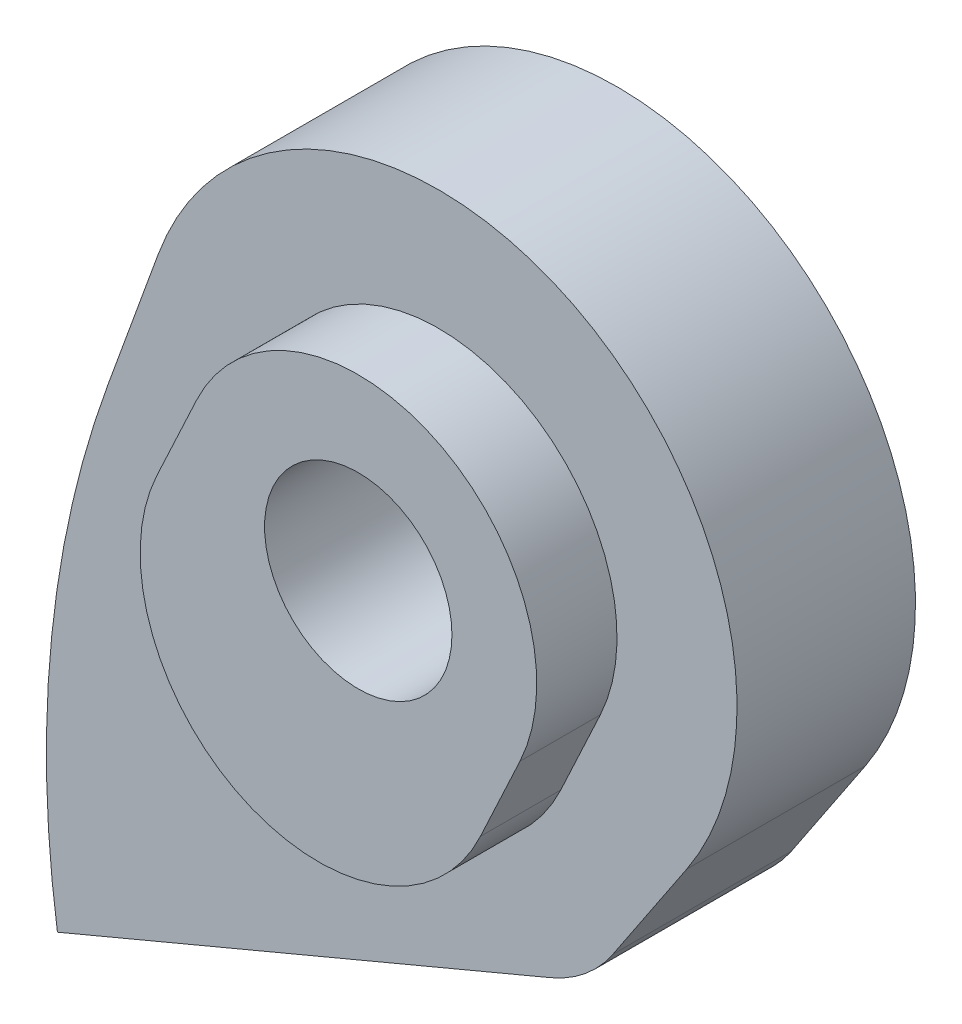
SolidWorks part; units mm, degrees
ref_plane "Front Plane" through (0, 0, 0) normal (0, 0, 1) x (1, 0, 0)
ref_plane "Top Plane" through (0, 0, 0) normal (0, 1, 0) x (1, 0, 0)
ref_plane "Right Plane" through (0, 0, 0) normal (1, 0, 0) x (0, 0, -1)
sketch "Sketch6" plane through (0, 0, 0) normal (0, 0, 1) x (1, 0, 0)
  line L0 (0, 0) -> (40.1809, 0) construction
  line L1 (0, 0) -> (35.507, 92.499) construction
  line L2 (19.3519, 50.4133) -> (0.4719, 63.0164) construction
  line L3 (19.3519, 50.4133) -> (-36.1025, 71.7003) construction
  dimension "D1" = 69
  dimension "D2" = 54
  dimension "D3" = 22.7
  dimension "D4" = 5
sketch "Sketch3" plane through (0, 0, 0) normal (0, 0, 1) x (1, 0, 0)
  line L0 (24.1743, 72.523) -> (120.8717, 72.523) construction
  line L6 (11.8164, 60.2529) -> (11.7284, 60.3116)
  line L7 (7.3748, 53.5992) -> (5.9136, 54.5745)
  line L8 (19.3519, 50.4133) -> (0.4719, 63.0164) construction
  line L9 (-6.1719, 82.4206) -> (-7.2903, 79.3479)
  line L10 (19.3519, 50.4133) -> (13.2479, 41.2693) construction
  line L11 (19.3519, 50.4133) -> (31.6629, 68.8558) construction
  line L12 (4.0204, 73.9337) -> (5.6789, 76.4182)
  line L14 (0.1147, 80.1325) -> (27.1455, 62.0885) construction
  line L15 (0.1147, 80.1325) -> (-7.2903, 79.3479) construction
  line L16 (0.1147, 80.1325) -> (0.1147, 91.1913) construction
  line L17 (0.1147, 80.1325) -> (-6.1719, 82.4206) construction
  arc A0 (13.4996, 47.0498) -> (20.2139, 57.1081) centre (19.3519, 50.4133) ccw
  arc A1 (20.2139, 57.1081) -> (11.8164, 60.2529) centre (22.7223, 76.5904) cw
  arc A2 (13.4996, 47.0498) -> (7.3748, 53.5992) centre (-3.5311, 37.2616) ccw
  arc A3 (11.7284, 60.3116) -> (6.8662, 65.9311) centre (19.4923, 71.9424) cw
  arc A4 (-6.1719, 82.4206) -> (5.6789, 76.4182) centre (0.1147, 80.1325) cw
  arc A5 (6.8662, 65.9311) -> (4.9012, 68.3908) centre (0.6246, 62.9595) ccw
  arc A6 (4.9012, 68.3908) -> (4.0204, 73.9337) centre (7.4585, 71.6386) cw
  arc A7 (5.9136, 54.5745) -> (0.4148, 56.2666) centre (0.3298, 46.2096) ccw
  arc A10 (0.4148, 56.2666) -> (-5.2798, 59.4837) centre (0.4719, 63.0164) cw
  circle A12 centre (19.3519, 50.4133) radius 2.75
  circle A13 centre (0.4719, 63.0164) radius 2.75
  circle A17 centre (0.1147, 80.1325) radius 2.1
  arc A18 (-7.2903, 79.3479) -> (-5.2798, 59.4837) centre (14.2795, 71.4971) ccw
  dimension "D1" = 5.5
  dimension "D2" = 5.5
  dimension "D3" = 4
  dimension "D5" = 4
  dimension "D6" = 4
  dimension "D4" = 4.2
  dimension "D17" = 70
  dimension "D18" = 3.27
  dimension "D14" = 6.69
  dimension "D7" = 3
  dimension "D8" = 4
  dimension "D9" = 3
  dimension "D10" = 4
  dimension "D11" = 19
  dimension "D12" = 19
  dimension "D13" = 22
  dimension "D15" = 32.5
  dimension "D16" = 14
extrude "Boss-Extrude2" add sketch "Sketch3" along normal blind 11
sketch "Sketch13" plane through (0, 0, 0) normal (0, 0, -1) x (-1, 0, 0)
  line L0 (-5.6789, 76.4182) -> (-4.0204, 73.9337)
  line L1 (-2.6258, 72.7829) -> (8.4277, 68.1397)
  line L2 (6.1719, 82.4206) -> (7.2903, 79.3479)
  arc A0 (-5.6789, 76.4182) -> (6.1719, 82.4206) centre (-0.1147, 80.1325) cw
  arc A1 (6.1719, 82.4206) -> (-5.6789, 76.4182) centre (-0.1147, 80.1325) ccw construction
  arc A2 (-4.0204, 73.9337) -> (-2.6258, 72.7829) centre (-1.4106, 75.6758) ccw
  arc A3 (5.2798, 59.4837) -> (7.2903, 79.3479) centre (-14.2795, 71.4971) ccw construction
  arc A4 (8.4277, 68.1397) -> (7.2903, 79.3479) centre (-14.2795, 71.4971) ccw
extrude "Boss-Extrude4" add sketch "Sketch13" along normal blind 4
sketch "Sketch12" plane through (0, 0, -4) normal (0, 0, -1) x (-1, 0, 0)
  line L0 (8.0136, 76.9658) -> (4.9242, 69.6114)
  line L4 (4.9242, 69.6114) -> (8.4277, 68.1397)
  line L5 (-2.6258, 72.7829) -> (8.4277, 68.1397) construction
  line L8 (-2.6258, 72.7829) -> (8.4277, 68.1397) construction
  arc A0 (8.0136, 76.9658) -> (8.4277, 68.1397) centre (-14.2795, 71.4971) cw
  arc A1 (5.2798, 59.4837) -> (8.4277, 68.1397) centre (-14.2795, 71.4971) ccw construction
  dimension "D1" = 3.8
  dimension "D2" = 90
extrude "Boss-Extrude3" add sketch "Sketch12" along normal blind 3
sketch "Sketch14" plane through (0, 0, 0) normal (0, 1, 0) x (1, 0, 0)
  line L0 (19.3519, 0) -> (-36.1025, 0) construction
  line L1 (-15.2308, 0) -> (32.0549, 0)
  line L2 (-15.2308, 0) -> (-15.2308, -12.5955)
  line L3 (-15.2308, -12.5955) -> (32.0549, -12.5955)
  line L4 (32.0549, 0) -> (32.0549, -12.5955)
extrude "Cut-Extrude1" cut sketch "Sketch14" along normal through all
sketch "Sketch16" plane through (0, 0, 0) normal (0, 0, 1) x (1, 0, 0)
  line L0 (0.1147, 80.1325) -> (-0.7728, 78.2293) construction
  line L1 (3.7399, 78.4421) -> (2.8524, 76.5388)
  line L2 (-3.5105, 81.823) -> (-4.398, 79.9198)
  line L3 (0.1147, 80.1325) -> (0.1147, 75.6752) construction
  arc A0 (3.7399, 78.4421) -> (-3.5105, 81.823) centre (0.1147, 80.1325) ccw
  arc A1 (-4.398, 79.9198) -> (2.8524, 76.5388) centre (-0.7728, 78.2293) ccw
  point P3 (-0.3291, 79.1809)
  dimension "D1" = 4
  dimension "D2" = 25
  dimension "D3" = 2.1
extrude "Boss-Extrude5" add sketch "Sketch16" along normal blind 1.8
sketch "Sketch15" plane through (0, 0, 1.8) normal (0, 0, 1) x (1, 0, 0)
  circle A0 centre (0.1147, 80.1325) radius 2.1
  dimension "D1" = 4.2
extrude "Cut-Extrude2" cut sketch "Sketch15" against normal through all
